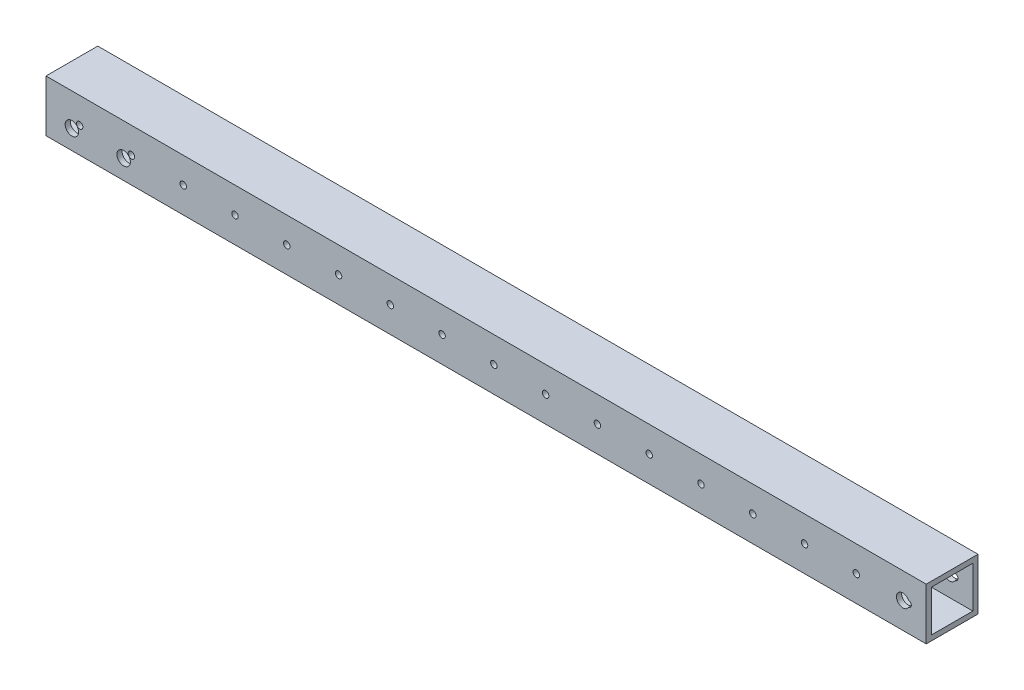
SolidWorks part; units mm, degrees
ref_plane "Front Plane" through (0, 0, 0) normal (0, 0, 1) x (1, 0, 0)
ref_plane "Top Plane" through (0, 0, 0) normal (0, 1, 0) x (1, 0, 0)
ref_plane "Right Plane" through (0, 0, 0) normal (1, 0, 0) x (0, 0, -1)
sketch "Sketch1" plane through (0, 0, 0) normal (0, 1, 0) x (1, 0, 0)
  line L1 (-90.932, 12.446) -> (340.868, 12.446)
  line L2 (-90.932, 12.446) -> (-90.932, -12.954)
  line L3 (-90.932, -12.954) -> (340.868, -12.954)
  line L4 (340.868, 12.446) -> (340.868, -12.954)
  dimension "D1" = 25.4
  dimension "D2" = 431.8
extrude "Boss-Extrude1" add sketch "Sketch1" along normal blind 25.4
sketch "Sketch2" plane through (-90.932, 0, 0) normal (-1, 0, 0) x (0, 0, 1)
  line L0 (-12.446, 25.4) -> (-12.446, 0) construction
  line L1 (-9.906, 2.54) -> (10.414, 2.54)
  line L2 (-9.906, 2.54) -> (-9.906, 22.86)
  line L3 (-9.906, 22.86) -> (10.414, 22.86)
  line L4 (10.414, 2.54) -> (10.414, 22.86)
  line L5 (-12.446, 0) -> (12.954, 0) construction
  line L6 (12.954, 25.4) -> (12.954, 0) construction
  line L7 (-12.446, 25.4) -> (12.954, 25.4) construction
  dimension "D1" = 2.54
  dimension "D2" = 2.54
  dimension "D3" = 2.54
  dimension "D4" = 2.54
extrude "Cut-Extrude1" cut sketch "Sketch2" against normal through all
sketch "Sketch3" plane through (0, 12.446, 12.954) normal (0, 0, -1) x (1, 0, 0)
  line L1 (-74.422, -0.254) -> (-49.022, -0.254) construction
  line L2 (-90.932, -12.954) -> (-90.932, 12.446) construction
  circle A0 centre (-74.422, -0.254) radius 1.5875
  circle A1 centre (-49.022, -0.254) radius 1.5875
  circle A2 centre (-23.622, -0.254) radius 1.5875
  circle A3 centre (1.778, -0.254) radius 1.5875
  circle A4 centre (27.178, -0.254) radius 1.5875
  circle A5 centre (52.578, -0.254) radius 1.5875
  circle A6 centre (77.978, -0.254) radius 1.5875
  circle A7 centre (103.378, -0.254) radius 1.5875
  circle A8 centre (128.778, -0.254) radius 1.5875
  circle A9 centre (154.178, -0.254) radius 1.5875
  circle A10 centre (179.578, -0.254) radius 1.5875
  circle A11 centre (204.978, -0.254) radius 1.5875
  circle A12 centre (230.378, -0.254) radius 1.5875
  circle A13 centre (255.778, -0.254) radius 1.5875
  circle A14 centre (281.178, -0.254) radius 1.5875
  circle A15 centre (306.578, -0.254) radius 1.5875
  circle A16 centre (331.978, -0.254) radius 1.5875
  point P2 (-90.932, -0.254)
  dimension "D1" = 3.175
  dimension "D2" = 16.51
  dimension "D4" = 25.4
  dimension "D3" = 17
extrude "Cut-Extrude2" cut sketch "Sketch3" along normal up to surface (25.4 mm away) up to face at (124.968, 12.7, -12.446)
sketch "Sketch4" plane through (0, 0, 12.954) normal (0, 0, 1) x (1, 0, 0)
  circle A0 centre (329.438, 12.7638) radius 3.175 construction
  circle A1 centre (-78.232, 9.525) radius 3.302 construction
  circle A2 centre (-52.832, 9.525) radius 3.302 construction
  circle A3 centre (329.438, 12.7638) radius 3.175
  circle A4 centre (-78.232, 9.525) radius 3.302
  circle A5 centre (-52.832, 9.525) radius 3.302
extrude "Cut-Extrude3" cut sketch "Sketch4" against normal up to surface (25.4 mm away) up to face at (-47.4345, 12.7, -12.446)
